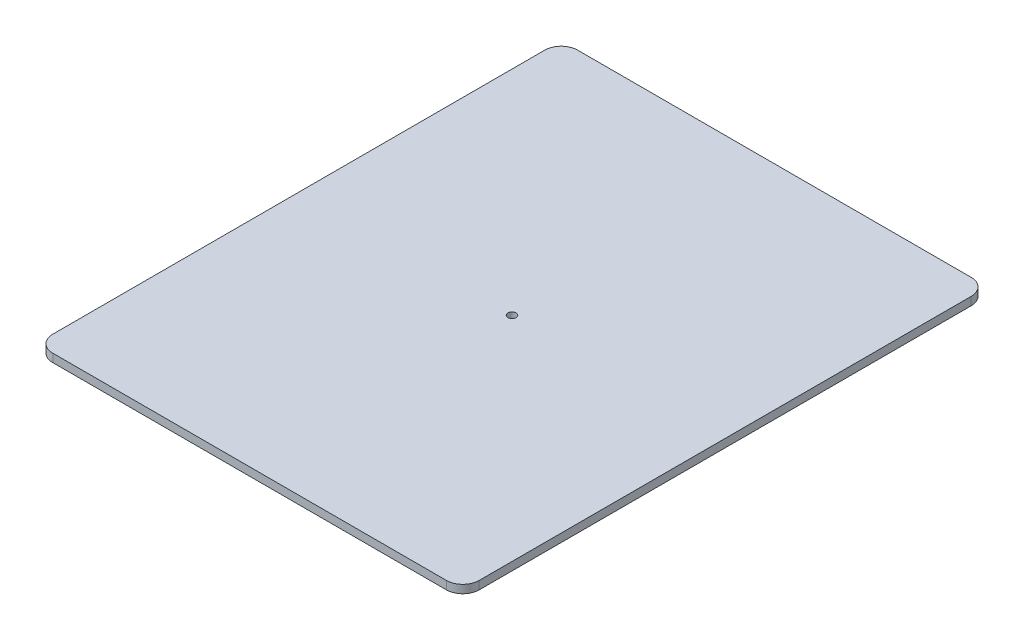
SolidWorks part; units mm, degrees
ref_plane "Front Plane" through (0, 0, 0) normal (0, 0, 1) x (1, 0, 0)
ref_plane "Top Plane" through (0, 0, 0) normal (0, 1, 0) x (1, 0, 0)
ref_plane "Right Plane" through (0, 0, 0) normal (1, 0, 0) x (0, 0, -1)
sketch "Sketch1" plane through (0, 0, 0) normal (0, 1, 0) x (1, 0, 0)
  line L1 (130, -160) -> (-130, -160)
  line L2 (130, -160) -> (130, 160)
  line L3 (130, 160) -> (-130, 160)
  line L4 (-130, -160) -> (-130, 160)
  line L5 (130, -160) -> (-130, 160) construction
  line L6 (130, 160) -> (-130, -160) construction
  point P0 (0, 0)
  dimension "D1" = 260
  dimension "D2" = 320
extrude "Boss-Extrude1" add sketch "Sketch1" along normal blind 5
fillet "Fillet1" radius 10 4 edges at (-130, 2.5, -160) (130, 2.5, -160) (-130, 2.5, 160) (130, 2.5, 160)
sketch "Sketch2" plane through (0, 5, 0) normal (0, 1, 0) x (1, 0, 0)
  circle A0 centre (0, 0) radius 2.5
  dimension "D1" = 5
extrude "Cut-Extrude1" cut sketch "Sketch2" against normal through all
